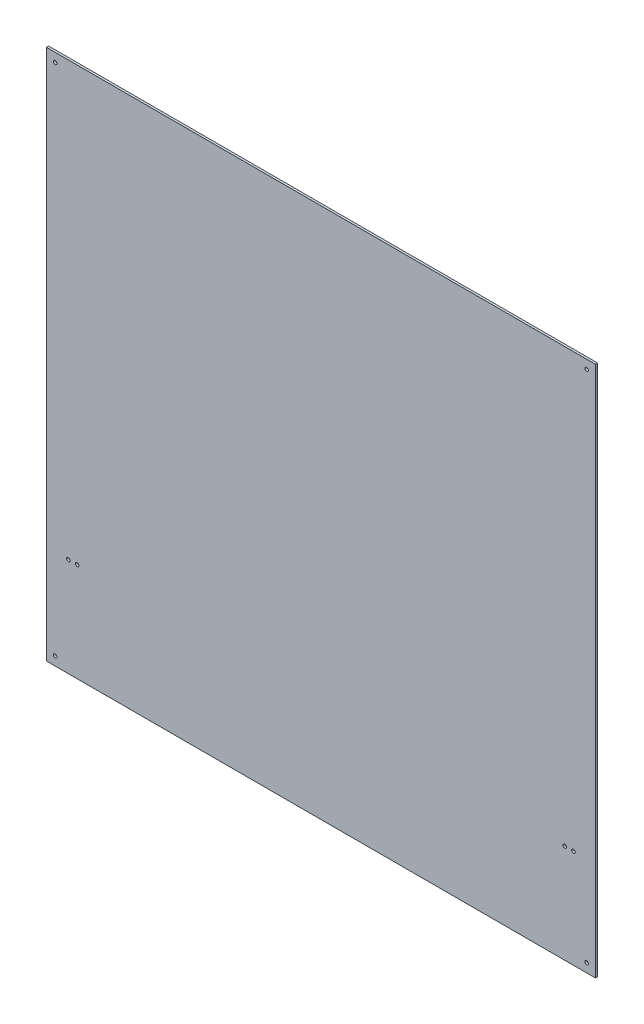
SolidWorks part; units mm, degrees
ref_plane "前视基准面" through (0, 0, 0) normal (0, 0, 1) x (1, 0, 0)
ref_plane "上视基准面" through (0, 0, 0) normal (0, 1, 0) x (1, 0, 0)
ref_plane "右视基准面" through (0, 0, 0) normal (1, 0, 0) x (0, 0, -1)
sketch "草图1" plane through (0, 0, 0) normal (0, 0, 1) x (1, 0, 0)
  line L1 (-653.5664, 554.6726) -> (596.4336, 554.6726)
  line L2 (-653.5664, 554.6726) -> (-653.5664, -655.3274)
  line L3 (-653.5664, -655.3274) -> (596.4336, -655.3274)
  line L4 (596.4336, 554.6726) -> (596.4336, -655.3274)
  dimension "D1" = 1250
  dimension "D2" = 1210
extrude "凸台-拉伸1" add sketch "草图1" along normal blind 5 contours L1 L4 L3 L2
sketch "草图2" plane through (0, 0, 5) normal (0, 0, 1) x (1, 0, 0)
  line L0 (-653.5664, 554.6726) -> (596.4336, 554.6726) construction
  line L2 (-653.5664, 554.6726) -> (-653.5664, -655.3274) construction
  circle A0 centre (-633.5664, 534.6726) radius 4.05
  circle A1 centre (576.4336, 534.6726) radius 4.05
  circle A2 centre (576.4336, -635.3274) radius 4.05
  circle A3 centre (-633.5664, -635.3274) radius 4.05
  dimension "D1" = 20
  dimension "D2" = 20
  dimension "D3" = 2
  dimension "D4" = 2
extrude "切除-拉伸1" cut sketch "草图2" against normal blind 5
sketch "草图3" plane through (0, 0, 5) normal (0, 0, 1) x (1, 0, 0)
  line L0 (-653.5664, 554.6726) -> (-653.5664, -655.3274) construction
  line L1 (-653.5664, -655.3274) -> (596.4336, -655.3274) construction
  line L2 (596.4336, 554.6726) -> (596.4336, -655.3274) construction
  circle A0 centre (-603.5664, -430.3274) radius 4.05
  circle A1 centre (526.4336, -430.3274) radius 4.05
  circle A2 centre (-583.5664, -430.3274) radius 4.05
  circle A3 centre (546.4336, -430.3274) radius 4.05
  point P6 (513.4386, -430.3274)
  point P13 (562.8581, -430.3274)
  dimension "D1" = 50
  dimension "D2" = 225
  dimension "D3" = 50
  dimension "D5" = 20
  dimension "D4" = 2
extrude "切除-拉伸2" cut sketch "草图3" against normal blind 5
